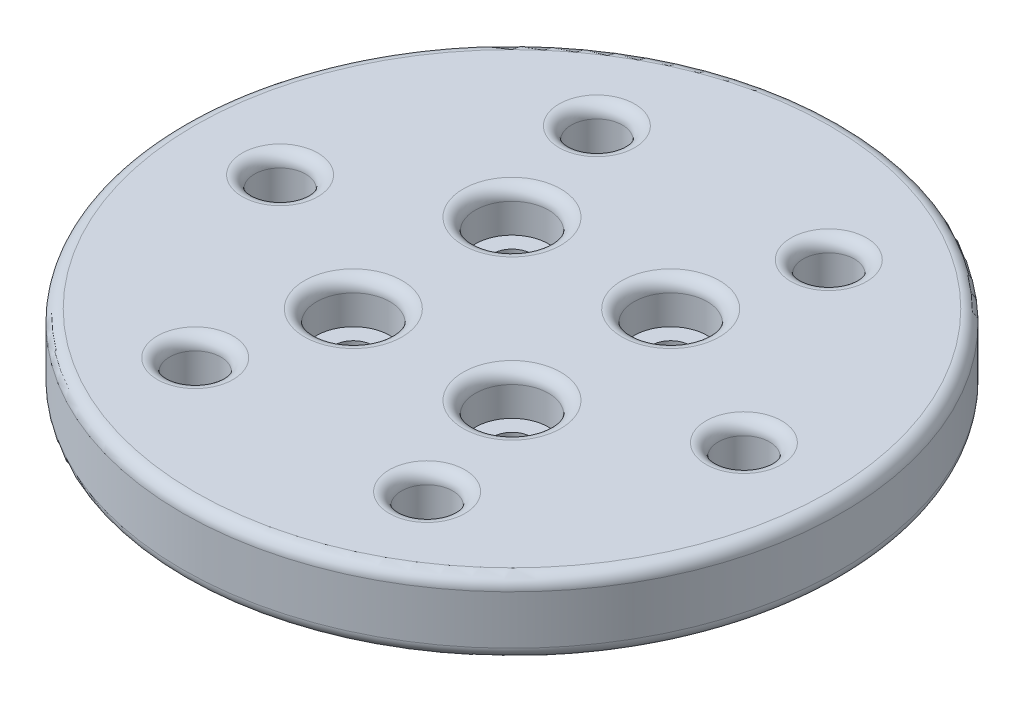
SolidWorks part; units mm, degrees
material "Thornel Mat VMA"
ref_plane "前视基准面" through (0, 0, 0) normal (0, 0, 1) x (1, 0, 0)
ref_plane "上视基准面" through (0, 0, 0) normal (0, 1, 0) x (1, 0, 0)
ref_plane "右视基准面" through (0, 0, 0) normal (1, 0, 0) x (0, 0, -1)
other "Configuration Table"
sketch "草图1" plane through (0, 0, 0) normal (0, 1, 0) x (1, 0, 0)
  circle A0 centre (0, 0) radius 27
  circle A1 centre (19, 0) radius 2.1
  circle A2 centre (9.5, -16.4545) radius 2.1
  circle A3 centre (-9.5, -16.4545) radius 2.1
  circle A4 centre (-19, 0) radius 2.1
  circle A5 centre (-9.5, 16.4545) radius 2.1
  circle A6 centre (9.5, 16.4545) radius 2.1
  point P17 (0, 0)
  dimension "D1" = 54
  dimension "D2" = 4.2
  dimension "D3" = 19
  dimension "D4" = 6
extrude "凸台-拉伸1" add sketch "草图1" along normal blind 6
sketch "草图2" plane through (0, 6, 0) normal (0, 1, 0) x (1, 0, 0)
  circle A2 centre (6.5, 6.5) radius 1.6
  circle A9 centre (6.5, -6.5) radius 1.6
  circle A10 centre (-6.5, -6.5) radius 1.6
  circle A11 centre (-6.5, 6.5) radius 1.6
  point P12 (0, 0)
  dimension "D1" = 3.2
  dimension "D3" = 6.5
  dimension "D2" = 6.5
extrude "切除-拉伸1" cut sketch "草图2" against normal through all
sketch "草图3" plane through (0, 6, 0) normal (0, 1, 0) x (1, 0, 0)
  circle A0 centre (6.5, 6.5) radius 3
  circle A1 centre (6.5, -6.5) radius 3
  circle A2 centre (-6.5, -6.5) radius 3
  circle A3 centre (-6.5, 6.5) radius 3
  point P12 (0, 0)
  dimension "D1" = 6
extrude "切除-拉伸2" cut sketch "草图3" against normal blind 3.4
fillet "圆角2" radius 1 22 edges at (9.5, 0, -14.3545) (-9.5, 0, -14.3545) (-19, 0, 2.1) (-9.5, 0, 18.5545) (9.5, 0, 18.5545) (19, 0, 2.1) (0, 0, 27) (6.5, 0, -4.9) (6.5, 0, 8.1) (-6.5, 0, 8.1) (-6.5, 0, -4.9) (9.5, 6, -14.3545) (-19, 6, 2.1) (9.5, 6, 18.5545) (0, 6, 27) (19, 6, 2.1) (-9.5, 6, 18.5545) (-9.5, 6, -14.3545) (6.5, 6, -3.5) (6.5, 6, 9.5) (-6.5, 6, 9.5) (-6.5, 6, -3.5)
